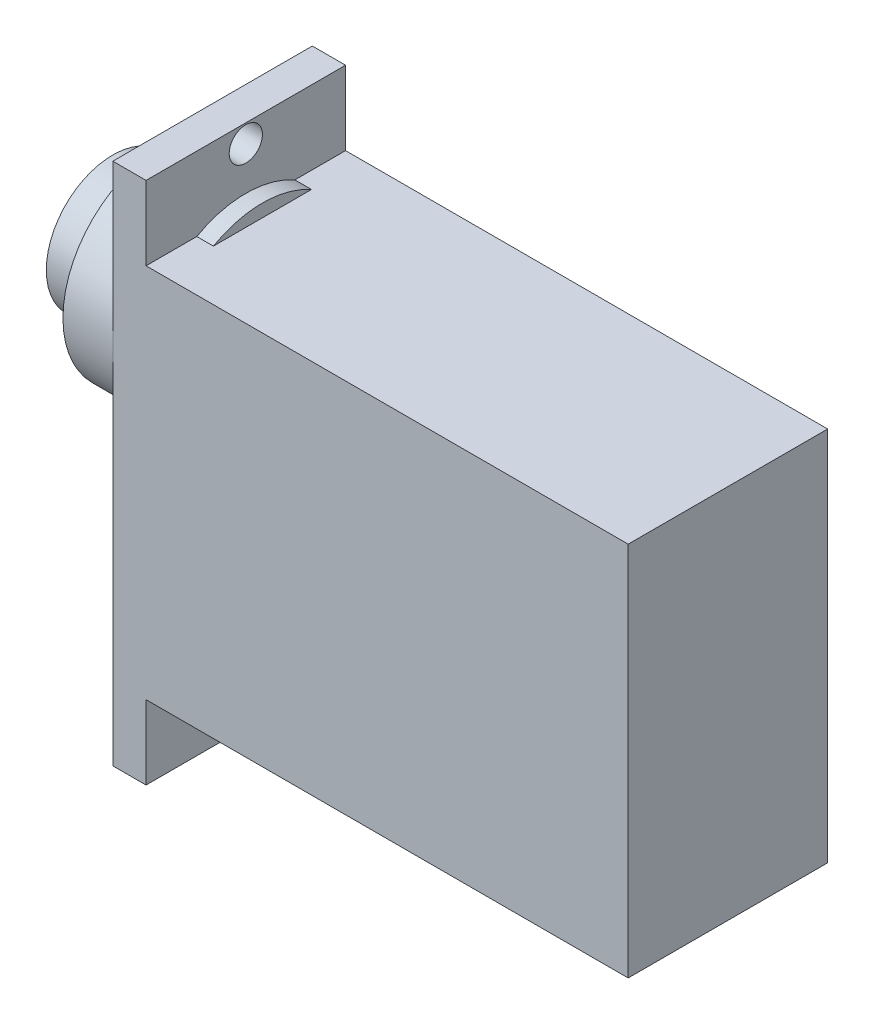
SolidWorks part; units mm, degrees
ref_plane "Front Plane" through (0, 0, 0) normal (0, 0, 1) x (1, 0, 0)
ref_plane "Top Plane" through (0, 0, 0) normal (0, 1, 0) x (1, 0, 0)
ref_plane "Right Plane" through (0, 0, 0) normal (1, 0, 0) x (0, 0, -1)
sketch "Sketch1" plane through (0, 0, 0) normal (0, 1, 0) x (1, 0, 0)
  line L1 (-15.5, -6) -> (15.5, -6)
  line L2 (-15.5, -6) -> (-15.5, 6)
  line L3 (-15.5, 6) -> (15.5, 6)
  line L4 (15.5, -6) -> (15.5, 6)
  line L5 (-15.5, -6) -> (15.5, 6) construction
  line L6 (-15.5, 6) -> (15.5, -6) construction
  point P0 (0, 0)
  dimension "D1" = 12
  dimension "D2" = 31
extrude "Boss-Extrude1" add sketch "Sketch1" along normal mid plane 22.6
sketch "Sketch3" plane through (0, 0, -6) normal (0, 0, -1) x (-1, 0, 0)
  line L0 (15.5, 11.3) -> (-15.5, 11.3) construction
  line L1 (15.5, 15.75) -> (13.5, 15.75)
  line L2 (15.5, 15.75) -> (15.5, 11.3)
  line L3 (15.5, 11.3) -> (13.5, 11.3)
  line L4 (13.5, 15.75) -> (13.5, 11.3)
  line L5 (15.5, 15.75) -> (13.5, 11.3) construction
  line L6 (15.5, 11.3) -> (13.5, 15.75) construction
  line L7 (15.5, 11.3) -> (15.5, -11.3) construction
  point P0 (14.5, 13.525)
  point P7 (0, 0)
  point P9 (0, 0)
  dimension "D1" = 2
  dimension "D2" = 4.45
extrude "Boss-Extrude2" add sketch "Sketch3" against normal blind 12
sketch "Sketch4" plane through (0, 0, -6) normal (0, 0, -1) x (-1, 0, 0)
  line L0 (-15.5, -11.3) -> (15.5, -11.3) construction
  line L1 (15.5, -11.3) -> (13.5, -11.3)
  line L2 (15.5, -11.3) -> (15.5, -15.75)
  line L3 (15.5, -15.75) -> (13.5, -15.75)
  line L4 (13.5, -11.3) -> (13.5, -15.75)
  line L5 (15.5, -11.3) -> (13.5, -15.75) construction
  line L6 (15.5, -15.75) -> (13.5, -11.3) construction
  line L7 (15.5, 15.75) -> (15.5, -11.3) construction
  point P0 (14.5, -13.525)
  dimension "D1" = 2
  dimension "D2" = 4.45
extrude "Boss-Extrude3" add sketch "Sketch4" against normal blind 12
sketch "Sketch5" plane through (-15.5, 0, 0) normal (-1, 0, 0) x (0, 0, 1)
  line L1 (6, 15.75) -> (-6, 15.75) construction
  line L2 (6, -15.75) -> (-6, -15.75) construction
  circle A0 centre (0, 14.65) radius 1
  circle A1 centre (0, -14.65) radius 1
  point P2 (0, 0)
  dimension "D1" = 2
  dimension "D2" = 1.1
  dimension "D3" = 1.1
extrude "Cut-Extrude1" cut sketch "Sketch5" against normal through all
sketch "Sketch6" plane through (-15.5, 0, 0) normal (-1, 0, 0) x (0, 0, 1)
  circle A0 centre (0, 6.0752) radius 6
  point P2 (0, 0)
  dimension "D1" = 12
extrude "Boss-Extrude4" add sketch "Sketch6" along normal mid plane 6
sketch "Sketch8" plane through (-18.5, 0, 0) normal (-1, 0, 0) x (0, 0, 1)
  circle A0 centre (0, 6.0752) radius 4
  dimension "D1" = 8
extrude "Boss-Extrude5" add sketch "Sketch8" along normal mid plane 6
